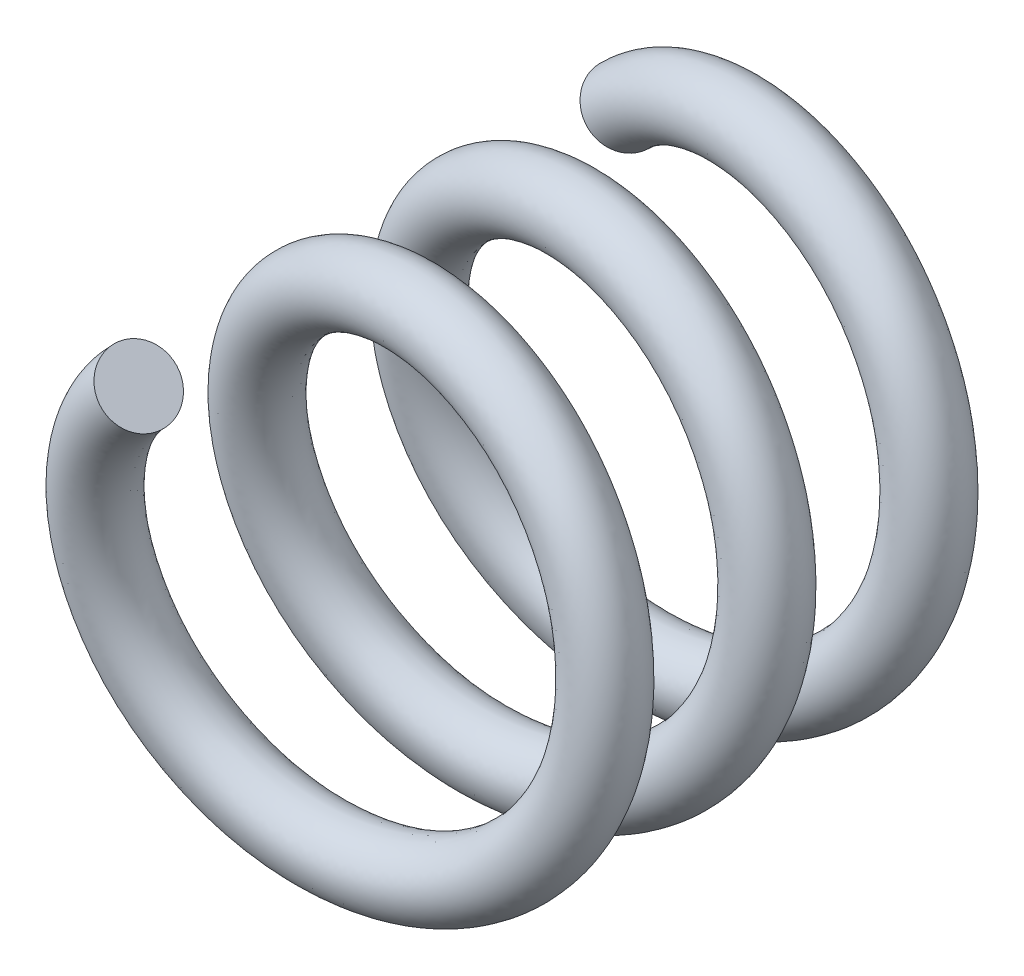
SolidWorks part; units mm, degrees
ref_plane "Front Plane" through (0, 0, 0) normal (0, 0, 1) x (1, 0, 0)
ref_plane "Top Plane" through (0, 0, 0) normal (0, 1, 0) x (1, 0, 0)
ref_plane "Right Plane" through (0, 0, 0) normal (1, 0, 0) x (0, 0, -1)
sketch "Sketch1" plane through (0, 0, 0) normal (0, 0, 1) x (1, 0, 0)
  circle A0 centre (0, 0) radius 3.065
  dimension "D1" = 6.13
curve "Helix/Spiral1" pitch 2.3333 height 7 turns 3
ref_plane "Plane2" through (-2.1673, 2.1673, 0) normal (0.702, 0.702, 0.1203) x (0.7122, -0.69, -0.1294)
sketch "Sketch3" plane through (-2.1673, 2.1673, 0) normal (0.702, 0.702, 0.1203) x (0.7122, -0.69, -0.1294)
  circle A0 centre (0, 0) radius 0.5
  dimension "D1" = 1
sweep "Sweep1" add profiles "Sketch3" path "Helix/Spiral1"
ref_plane "Plane3" through (0, 0, 0) normal (0, 0, 1) x (1, 0, 0)
ref_plane "Plane4" through (0, 0, 7) normal (0, 0, 1) x (1, 0, 0)
ref_plane "Plane5" through (0, 0, 7.5) normal (0, 0, 1) x (1, 0, 0)
ref_plane "Plane6" through (0, 0, -0.5) normal (0, 0, 1) x (1, 0, 0)
equation "\"spring_diameter\"=6.13"
equation "\"coil_diameter\"=1.00"
equation "\"number_of_coils\"=3"
equation "\"D1@Sketch1\"=\"spring_diameter\""
equation "\"spring_length\"=7"
equation "\"D3@Helix/Spiral1\"=\"spring_length\""
equation "\"D1@Sketch3\"=\"coil_diameter\""
equation "\"D1@Plane5\"=\"coil_diameter\"/2"
equation "\"D1@Plane6\"=\"coil_diameter\"/2"
